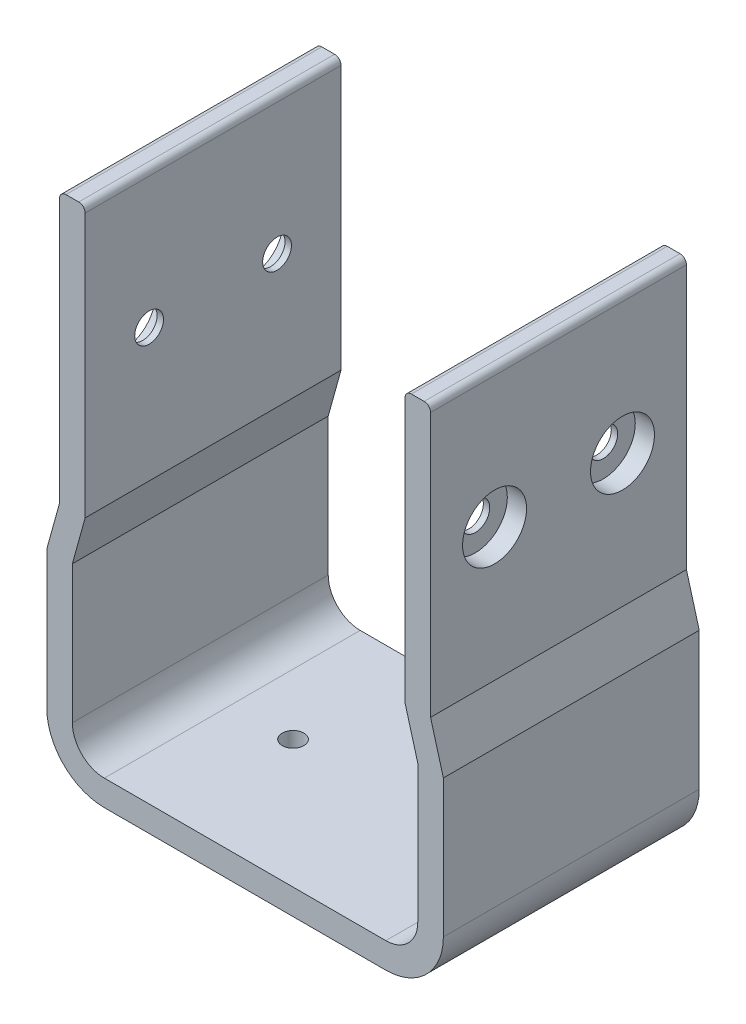
SolidWorks part; units mm, degrees
ref_plane "Piano frontale" through (0, 0, 0) normal (0, 0, 1) x (1, 0, 0)
ref_plane "Piano superiore" through (0, 0, 0) normal (0, 1, 0) x (1, 0, 0)
ref_plane "Piano destro" through (0, 0, 0) normal (1, 0, 0) x (0, 0, -1)
sketch "Schizzo1" plane through (0, 0, 0) normal (0, 0, 1) x (1, 0, 0)
  line L0 (9, 0) -> (53, 0)
  line L1 (62, 9) -> (62, 30.52)
  line L2 (62, 30.52) -> (58, 30.52) construction
  line L3 (58, 30.52) -> (58, 9)
  line L4 (53, 4) -> (9, 4)
  line L5 (4, 9) -> (4, 30.52)
  line L7 (0, 30.52) -> (0, 9)
  line L8 (4, 30.52) -> (6, 37.73)
  line L9 (6, 37.73) -> (6, 80)
  line L10 (6, 80) -> (2, 80)
  line L11 (2, 80) -> (2, 37.73)
  line L12 (2, 37.73) -> (0, 30.52)
  line L13 (0, 30.52) -> (4, 30.52) construction
  line L14 (2, 37.73) -> (6, 37.73) construction
  line L15 (62, 30.52) -> (60, 37.73)
  line L16 (60, 37.73) -> (60, 80)
  line L17 (60, 80) -> (56, 80)
  line L18 (56, 80) -> (56, 37.73)
  line L19 (56, 37.73) -> (58, 30.52)
  line L20 (56, 37.73) -> (60, 37.73) construction
  line L21 (6, 80) -> (56, 80) construction
  arc A0 (53, 0) -> (62, 9) centre (53, 9) ccw
  arc A1 (9, 0) -> (0, 9) centre (9, 9) cw
  arc A2 (53, 4) -> (58, 9) centre (53, 9) ccw
  arc A3 (9, 4) -> (4, 9) centre (9, 9) cw
  point P7 (62, 25.3821)
  point P18 (52.9994, 30.1555)
  point P19 (62, 24.0293)
  point P22 (62, 0)
  point P25 (0, 0)
  dimension "D9" = 9
  dimension "D10" = 5
  dimension "D1" = 2
  dimension "D2" = 7.21
  dimension "D3" = 62
  dimension "D4" = 4
  dimension "D5" = 4
  dimension "D6" = 4
  dimension "D7" = 4
  dimension "D8" = 42.27
  dimension "D11" = 80
extrude "Estrusione-Estrusione1" add sketch "Schizzo1" along normal blind 40
fillet "Raccordo1" radius 1 4 edges at (60, 80, 20) (56, 80, 20) (6, 80, 20) (2, 80, 20)
sketch "Schizzo2" plane through (2, 0, 0) normal (-1, 0, 0) x (0, 0, 1)
  line L0 (10, 58.5) -> (30, 58.5) construction
  line L2 (0, 79) -> (0, 37.73) construction
  line L3 (0, 80) -> (40, 80) construction
  point P0 (10, 58.5)
  point P2 (30, 58.5)
  dimension "D1" = 20
  dimension "D2" = 10
  dimension "D3" = 21.5
hole_wizard "Foro lamato per Bullone M12 a testa esagonale (Classe superiore)-1" positions "Schizzo2" profile "Schizzo3" counterbore size "M12" standard "DIN"
sketch "Schizzo3" plane through (2, 58.5, 10) normal (0, 1, 0) x (0, 0, 1)
  line L0 (0, 0) -> (0, 9.8519)
  line L1 (0, 9.8519) -> (2.25, 8.5)
  line L2 (2.25, 8.5) -> (2.25, 3)
  line L3 (2.25, 3) -> (5, 3)
  line L4 (5, 3) -> (5, 0)
  line L5 (5, 0) -> (0, 0)
  line L10 (0, 9.8519) -> (-2.25, 8.5) construction
  line L11 (0, -6.35) -> (0, 107.95) construction
  dimension "Hole Dia." = 4.5
  dimension "Hole Depth" = 8.5
  dimension "C'Bore Dia." = 10
  dimension "C'Bore Depth" = 3
  dimension "Drill Angle" = 118
hole_wizard "Foro lamato per Bullone M12 a testa esagonale (Classe superiore)-2" positions "Schizzo4" profile "Schizzo5" counterbore size "M12" standard "DIN"
sketch "Schizzo4" plane through (60, 0, 0) normal (1, 0, 0) x (0, 0, -1)
  line L0 (-30, 58.5) -> (-10, 58.5) construction
  line L2 (0, 37.73) -> (0, 79) construction
  line L3 (-40, 80) -> (0, 80) construction
  point P0 (-30, 58.5)
  point P2 (-10, 58.5)
  dimension "D1" = 10
  dimension "D2" = 20
  dimension "D3" = 21.5
sketch "Schizzo5" plane through (60, 58.5, 30) normal (0, 1, 0) x (0, 0, -1)
  line L0 (0, 0) -> (0, 9.8519)
  line L1 (0, 9.8519) -> (2.25, 8.5)
  line L2 (2.25, 8.5) -> (2.25, 3)
  line L3 (2.25, 3) -> (5, 3)
  line L4 (5, 3) -> (5, 0)
  line L5 (5, 0) -> (0, 0)
  line L10 (0, 9.8519) -> (-2.25, 8.5) construction
  line L11 (0, -6.35) -> (0, 107.95) construction
  dimension "Hole Dia." = 4.5
  dimension "Hole Depth" = 8.5
  dimension "C'Bore Dia." = 10
  dimension "C'Bore Depth" = 3
  dimension "Drill Angle" = 118
sketch "Schizzo6" plane through (0, 4, 0) normal (0, 1, 0) x (1, 0, 0)
  line L0 (9, -20) -> (53, -20) construction
  line L1 (9, -40) -> (9, 0) construction
  line L2 (53, -40) -> (53, 0) construction
  point P0 (18.5, -20)
  point P2 (43.5, -20)
  point P12 (42.4897, -20)
  point P13 (19.4417, -20)
  dimension "D1" = 25
  dimension "D2" = 9.5
hole_wizard "Foro per Vite M3-1" positions "Schizzo6" profile "Schizzo7" hole size "M3" standard "DIN"
sketch "Schizzo7" plane through (18.5, 4, 20) normal (1, 0, 0) x (0, 0, 1)
  line L0 (0, 0) -> (0, 9.5215)
  line L1 (0, 9.5215) -> (1.7, 8.5)
  line L2 (1.7, 8.5) -> (1.7, 0)
  line L5 (1.7, 0) -> (0, 0)
  line L10 (0, 9.5215) -> (-1.7, 8.5) construction
  line L11 (0, -6.35) -> (0, 107.95) construction
  dimension "Hole Dia." = 3.4
  dimension "Hole Depth" = 8.5
  dimension "Drill Angle" = 118
